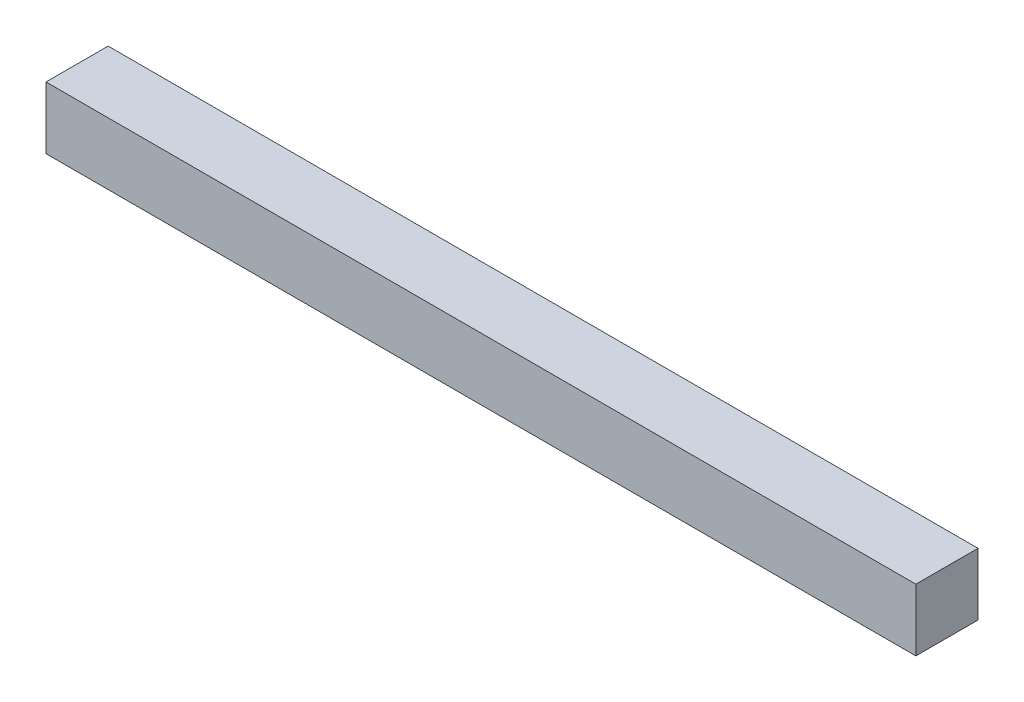
SolidWorks part; units mm, degrees
ref_plane "Front Plane" through (0, 0, 0) normal (0, 0, 1) x (1, 0, 0)
ref_plane "Top Plane" through (0, 0, 0) normal (0, 1, 0) x (1, 0, 0)
ref_plane "Right Plane" through (0, 0, 0) normal (1, 0, 0) x (0, 0, -1)
sketch "Belt Drive Axle" plane through (0, 0, 0) normal (0, 1, 0) x (1, 0, 0)
  line L1 (-44.45, -3.175) -> (44.45, -3.175)
  line L2 (-44.45, -3.175) -> (-44.45, 3.175)
  line L3 (-44.45, 3.175) -> (44.45, 3.175)
  line L4 (44.45, -3.175) -> (44.45, 3.175)
  line L5 (-44.45, -3.175) -> (44.45, 3.175) construction
  line L6 (-44.45, 3.175) -> (44.45, -3.175) construction
  point P0 (0, 0)
  dimension "D1" = 6.35
  dimension "D2" = 88.9
extrude "Boss-Extrude1" add sketch "Belt Drive Axle" along normal blind 6.35
equation "\"Ball Diameter\"= 1.75in"
equation "\"Sheet Thickness\"= 0.25in"
equation "\"Screw Diameter\"= .17in"
equation "\"Robot Diameter\"= 14in"
equation "\"Castor Screw Diameter\"= 0.22in"
equation "\"Wheel Diameter\" = 4in"
equation "\"Nut Diameter\" = 8.4mm"
equation "\"Nut Height\" = 2.9mm"
equation "\"Screw Height\" = 0.55in"
equation "\"Pulley Diameter\" = 1in"
equation "\"Reactor Height\" = 14in"
equation "\"D1@Belt Drive Axle\"=\"Sheet Thickness\""
equation "\"Elevator Height\" = 11.5in"
equation "\"Elevator Width\" = \"Ball Diameter\" + 0.25in"
equation "\"Elevator Axle Length\" = \"Elevator Width\" + 6*\"Sheet Thickness\""
equation "\"D2@Belt Drive Axle\"=\"Elevator Axle Length\""
equation "\"D1@Boss-Extrude1\"=\"Sheet Thickness\""
